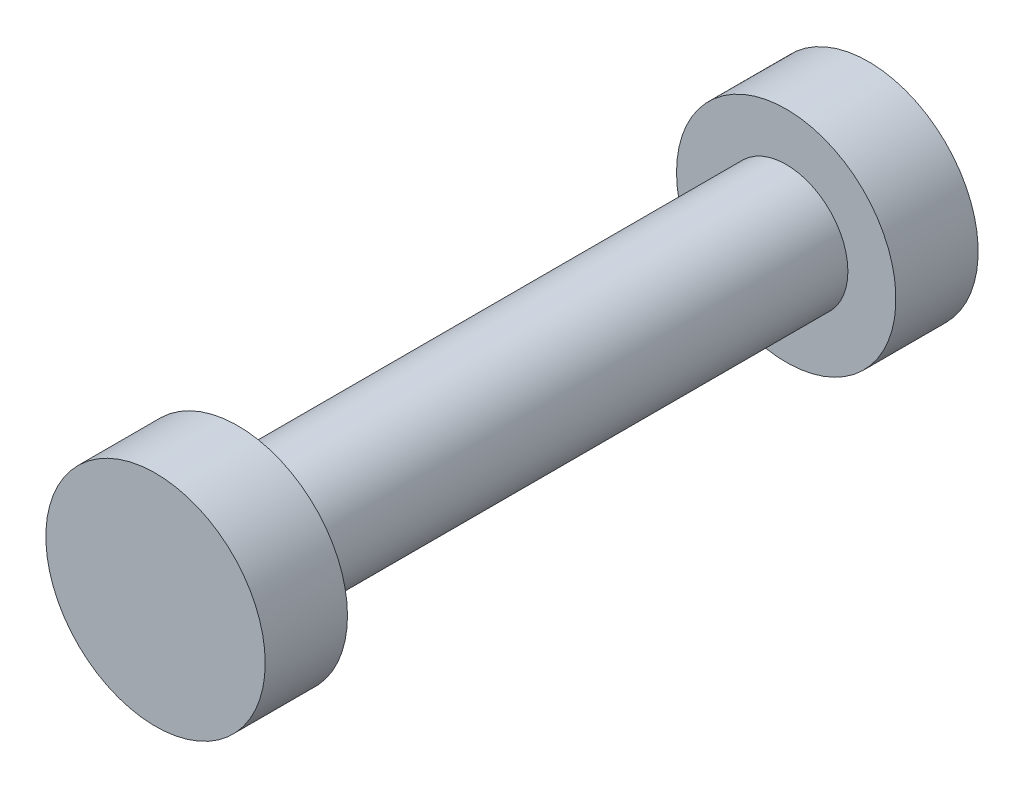
SolidWorks part; units mm, degrees
ref_plane "Alzado" through (0, 0, 0) normal (0, 0, 1) x (1, 0, 0)
ref_plane "Planta" through (0, 0, 0) normal (0, 1, 0) x (1, 0, 0)
ref_plane "Vista lateral" through (0, 0, 0) normal (1, 0, 0) x (0, 0, -1)
sketch "Croquis1" plane through (0, 0, 0) normal (0, 0, 1) x (1, 0, 0)
  circle A0 centre (0, 0) radius 2.25
  dimension "D1" = 4.5
extrude "Saliente-Extruir1" add sketch "Croquis1" along normal blind 20
sketch "Croquis2" plane through (0, 0, 20) normal (0, 0, 1) x (1, 0, 0)
  circle A0 centre (0, 0) radius 4
  dimension "D1" = 8
extrude "Saliente-Extruir2" add sketch "Croquis2" along normal blind 3
sketch "Croquis3" plane through (0, 0, 0) normal (0, 0, -1) x (-1, 0, 0)
  circle A0 centre (0, 0) radius 4 construction
  circle A1 centre (0, 0) radius 4
extrude "Saliente-Extruir3" add sketch "Croquis3" along normal blind 3
